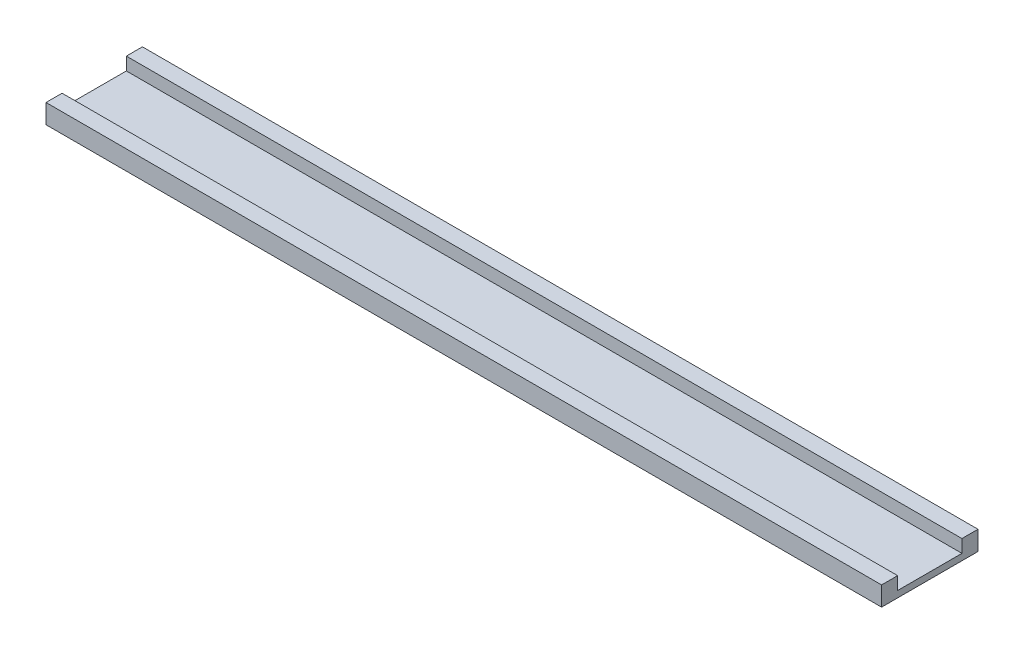
SolidWorks part; units mm, degrees
ref_plane "Ön Düzlem" through (0, 0, 0) normal (0, 0, 1) x (1, 0, 0)
ref_plane "Üst Düzlem" through (0, 0, 0) normal (0, 1, 0) x (1, 0, 0)
ref_plane "Sağ Düzlem" through (0, 0, 0) normal (1, 0, 0) x (0, 0, -1)
sketch "Çizim1" plane through (0, 0, 0) normal (0, 1, 0) x (1, 0, 0)
  line L1 (-65, 7.5) -> (65, 7.5)
  line L2 (-65, 7.5) -> (-65, -7.5)
  line L3 (-65, -7.5) -> (65, -7.5)
  line L4 (65, 7.5) -> (65, -7.5)
  point P0 (0, 0)
  dimension "D1" = 130
  dimension "D2" = 15
extrude "Yükseklik-Ekstrüzyon1" add sketch "Çizim1" along normal blind 3
sketch "Çizim2" plane through (0, 3, 0) normal (0, 1, 0) x (1, 0, 0)
  line L1 (-65, 5) -> (65, 5)
  line L2 (-65, 5) -> (-65, -5)
  line L3 (-65, -5) -> (65, -5)
  line L4 (65, 5) -> (65, -5)
  line L5 (-65, 5) -> (65, -5) construction
  line L6 (-65, -5) -> (65, 5) construction
  point P0 (0, 0)
  dimension "D1" = 130
  dimension "D2" = 10
extrude "Kes-Ekstrüzyon1" cut sketch "Çizim2" against normal blind 2
